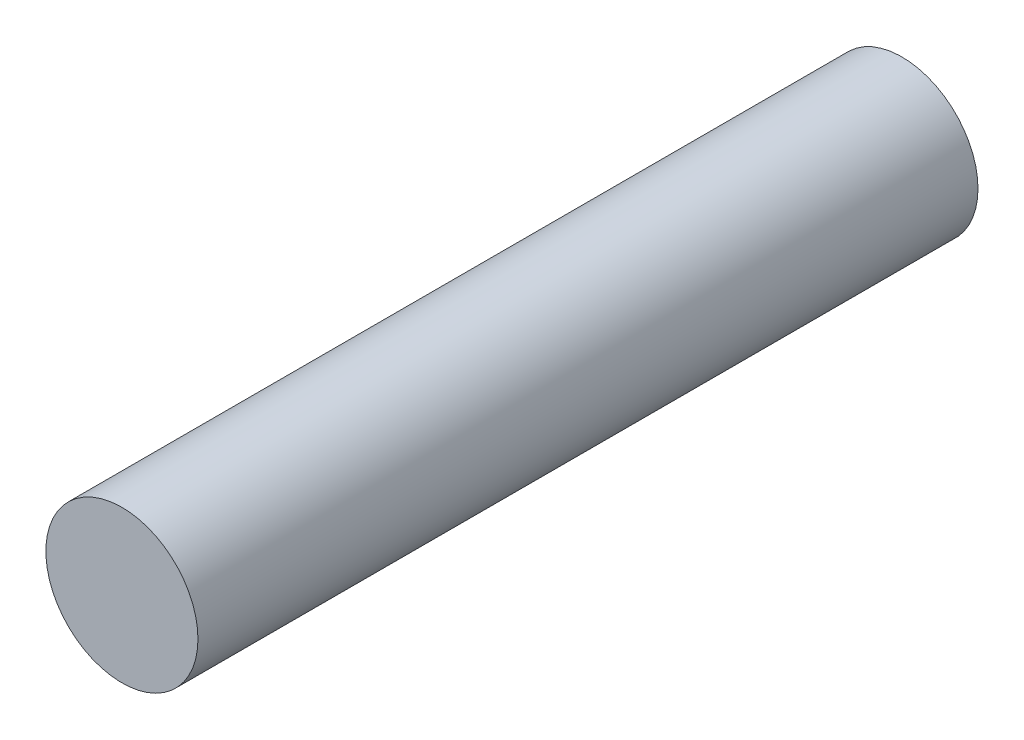
SolidWorks part; units mm, degrees
ref_plane "Front Plane" through (0, 0, 0) normal (0, 0, 1) x (1, 0, 0)
ref_plane "Top Plane" through (0, 0, 0) normal (0, 1, 0) x (1, 0, 0)
ref_plane "Right Plane" through (0, 0, 0) normal (1, 0, 0) x (0, 0, -1)
sketch "Sketch1" plane through (0, 0, 0) normal (0, 0, 1) x (1, 0, 0)
  circle A0 centre (0, 0) radius 2.4765
  dimension "D1" = 4.953
extrude "Boss-Extrude1" add sketch "Sketch1" along normal mid plane 25.4
